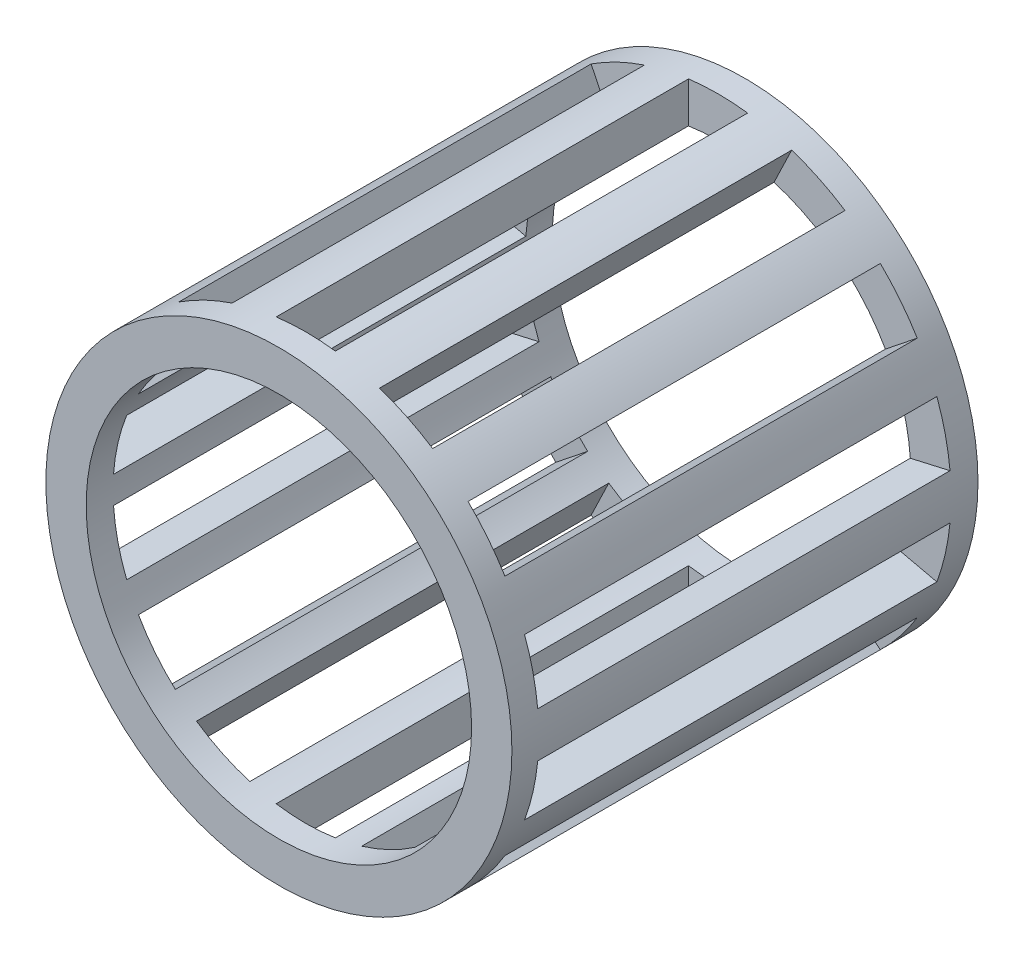
SolidWorks part; units mm, degrees
ref_plane "Front" through (0, 0, 0) normal (0, 0, 1) x (1, 0, 0)
ref_plane "Top" through (0, 0, 0) normal (0, 1, 0) x (1, 0, 0)
ref_plane "Right" through (0, 0, 0) normal (1, 0, 0) x (0, 0, -1)
sketch "Эскиз1" plane through (0, 0, 0) normal (0, 0, 1) x (1, 0, 0)
  circle A0 centre (0, 0) radius 5.375
  circle A1 centre (0, 0) radius 6.5
  dimension "D1" = 10.75
  dimension "D2" = 13
extrude "Бобышка-Вытянуть1" add sketch "Эскиз1" along normal blind 13
sketch "Эскиз2" plane through (0, 0, 0) normal (0, 1, 0) x (1, 0, 0)
  line L1 (-0.825, -0.75) -> (0.825, -0.75)
  line L2 (-0.825, -0.75) -> (-0.825, -12.25)
  line L3 (-0.825, -12.25) -> (0.825, -12.25)
  line L4 (0.825, -0.75) -> (0.825, -12.25)
  dimension "D1" = 1.65
  dimension "D2" = 0.825
  dimension "D3" = 11.5
  dimension "D4" = 0.75
extrude "Вырез-Вытянуть1" cut sketch "Эскиз2" against normal blind 6.5
pattern_circular "Круговой массив1" count 14 over 360 about axis through (0, 0, 0) along (0, 0, 1) of "Вырез-Вытянуть1"
